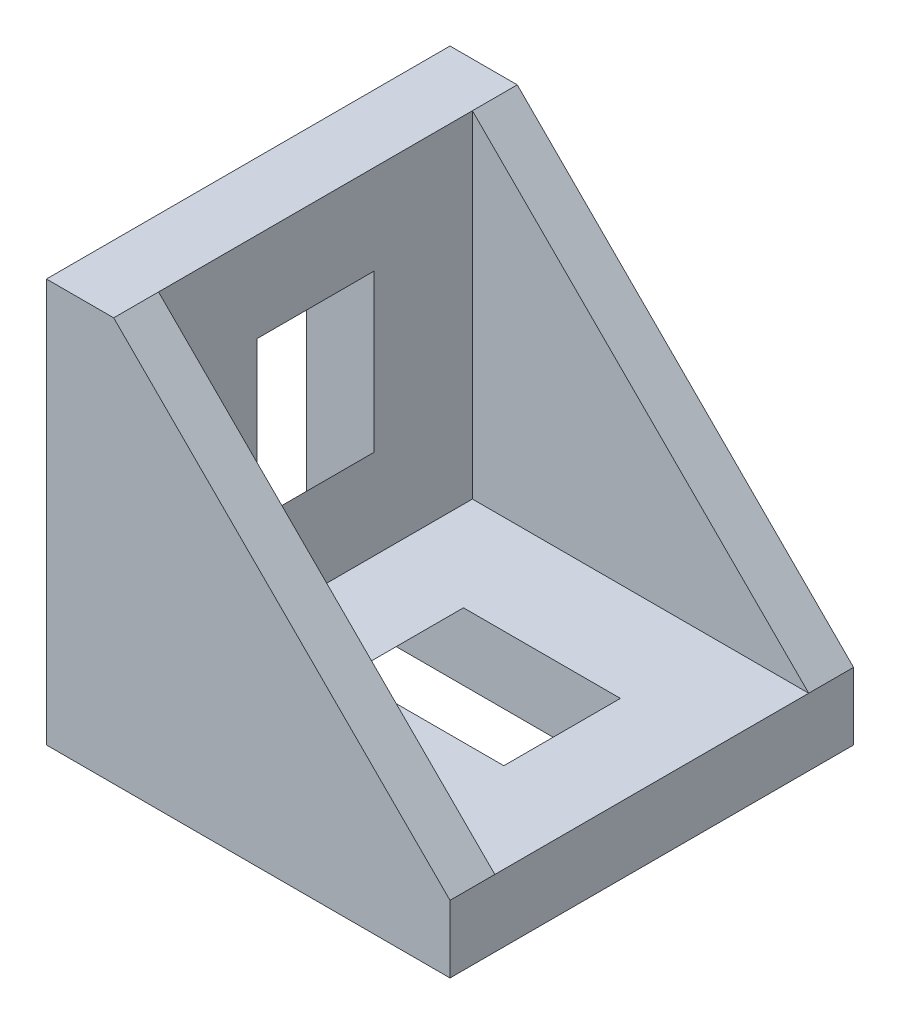
SolidWorks part; units mm, degrees
ref_plane "Front Plane" through (0, 0, 0) normal (0, 0, 1) x (1, 0, 0)
ref_plane "Top Plane" through (0, 0, 0) normal (0, 1, 0) x (1, 0, 0)
ref_plane "Right Plane" through (0, 0, 0) normal (1, 0, 0) x (0, 0, -1)
sketch "Sketch1" plane through (0, 0, 0) normal (0, 0, 1) x (1, 0, 0)
  line L0 (0, 0) -> (0, 18)
  line L1 (18, 3) -> (3, 18)
  line L4 (3, 18) -> (0, 18)
  line L5 (18, 0) -> (0, 0)
  line L7 (18, 3) -> (18, 0)
  dimension "D" = 3
  dimension "C" = 18
  dimension "B" = 18
extrude "Boss-Extrude1" add sketch "Sketch1" along normal mid plane 18
sketch "Sketch2" plane through (0, 0, 0) normal (0, 0, 1) x (1, 0, 0)
  line L0 (3, 18) -> (3, 3)
  line L1 (3, 3) -> (18, 3)
  line L2 (3, 18) -> (18, 3)
extrude "Cut-Extrude1" cut sketch "Sketch2" against normal mid plane 14
sketch "Sketch3" plane through (0, 0, 0) normal (0, 0, 1) x (1, 0, 0)
  line L0 (18, 3) -> (3, 18) construction
  line L1 (0, 14) -> (3, 14)
  line L2 (0, 14) -> (0, 4)
  line L3 (0, 4) -> (3, 7)
  line L4 (3, 14) -> (3, 7)
  line L5 (7, 3) -> (14, 3)
  line L6 (7, 3) -> (4, 0)
  line L7 (4, 0) -> (14, 0)
  line L8 (14, 3) -> (14, 0)
  line L10 (18, 0) -> (0, 0) construction
  line L11 (0, 0) -> (0, 18) construction
  dimension "D1" = 14
  dimension "D2" = 7
  dimension "D3" = 14
  dimension "D4" = 7
extrude "Cut-Extrude2" cut sketch "Sketch3" against normal mid plane 5.2
sketch "Sketch4" plane through (0, 0, 0) normal (0, 0, 1) x (1, 0, 0)
  line L0 (0, 18) -> (0, 0) construction
  line L1 (1.2115, 2.3429) -> (0, 1.2348) construction
  line L2 (1.5046, -1.8) -> (0.5112, -0.7909)
  line L3 (0, 3.5355) -> (-1.8, 1.5046)
  line L4 (-1.8, 1.5046) -> (-0.7909, 0.5112)
  line L5 (-0.7909, 0.5112) -> (0, 1.2348)
  line L6 (0, 1.2348) -> (0, 3.5355)
  line L7 (0.5112, -0.7909) -> (1.2348, 0)
  line L8 (0, 0) -> (0, 18) construction
  line L9 (-1.2955, 1.0079) -> (0, 2.3239) construction
  line L10 (1.2348, 0) -> (3.5355, 0)
  line L11 (3.5355, 0) -> (1.5046, -1.8)
  line L12 (0, 17.3) -> (0, 14.9992)
  line L13 (0, 14.9992) -> (-0.7909, 14.2757)
  line L14 (-0.7909, 14.2757) -> (-1.8, 15.269)
  line L15 (-1.8, 15.269) -> (0, 17.3)
  line L16 (-1.2955, 14.7724) -> (0, 16.0884) construction
  line L17 (0, 16.0884) -> (0.6057, 16.7037) construction
  line L18 (18, 3) -> (3, 18) construction
  line L19 (10.5, 10.5) -> (0, 0) construction
  line L20 (0, 17.3) -> (1.2115, 16.1074) construction
  line L21 (0, 14.9992) -> (1.2115, 16.1074) construction
  line L22 (0, 3.5355) -> (1.2115, 2.3429) construction
  line L23 (14.9992, 0) -> (14.2757, -0.7909)
  line L24 (0.6057, 2.9392) -> (0, 2.3239) construction
  line L25 (14.2757, -0.7909) -> (15.269, -1.8)
  line L26 (17.3, 0) -> (14.9992, 0)
  line L27 (15.269, -1.8) -> (17.3, 0)
  line L28 (-1.8, 1.5046) -> (-1.8, 15.269) construction
  dimension "D1" = 1.7
  dimension "D2" = 5
  dimension "D3" = 6
  dimension "D4" = 1.6001
  dimension "D5" = 0.7
  dimension "D6" = 0.1905
  dimension "D7" = 1.8
extrude "Boss-Extrude2" add sketch "Sketch4" along normal mid plane 6
